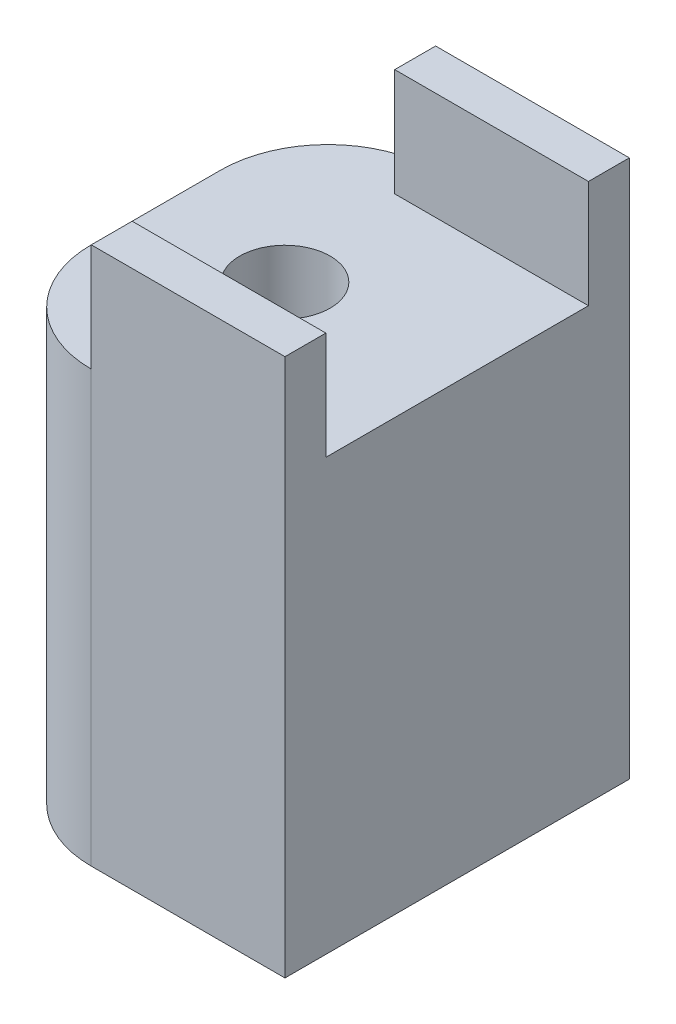
SolidWorks part; units mm, degrees
ref_plane "Front Plane" through (0, 0, 0) normal (0, 0, 1) x (1, 0, 0)
ref_plane "Top Plane" through (0, 0, 0) normal (0, 1, 0) x (1, 0, 0)
ref_plane "Right Plane" through (0, 0, 0) normal (1, 0, 0) x (0, 0, -1)
sketch "Sketch1" plane through (0, 0, 0) normal (0, 1, 0) x (1, 0, 0)
  line L5 (-6, 8) -> (6, 8)
  line L6 (-6, 8) -> (-6, -8)
  line L7 (-6, -8) -> (6, -8)
  line L8 (6, 8) -> (6, -8)
  line L9 (-6, 8) -> (6, -8) construction
  line L10 (-6, -8) -> (6, 8) construction
  line L11 (6, 8) -> (8, 8)
  line L12 (6, 8) -> (6, -8)
  line L13 (6, -8) -> (8, -8)
  line L14 (8, 8) -> (8, -8)
  circle A0 centre (0, 0) radius 2.1
  point P0 (0, 0)
  dimension "D1" = 4.2
  dimension "D2" = 16
  dimension "D3" = 6
  dimension "D4" = 2
extrude "Boss-Extrude1" add sketch "Sketch1" along normal blind 20 contours L8 L5 L6 L7 A0 | L14 L11 L8 L13
fillet "Fillet1" radius 5 2 edges at (-6, 10, -8) (-6, 10, 8)
sketch "Sketch2" plane through (0, 20, 0) normal (0, 1, 0) x (1, 0, 0)
  line L0 (8, 0) -> (-6, 0) construction
  line L1 (8, 8) -> (-1, 8)
  line L2 (8, 8) -> (8, 6.1)
  line L3 (8, 6.1) -> (-1, 6.1)
  line L4 (-1, 8) -> (-1, 6.1)
  line L5 (8, 8) -> (8, -8) construction
  line L6 (-6, 3) -> (-6, -3) construction
  line L7 (-1, -8) -> (-1, -6.1)
  line L8 (8, -6.1) -> (-1, -6.1)
  line L9 (8, -8) -> (8, -6.1)
  line L10 (8, -8) -> (-1, -8)
  dimension "D1" = 1.9
extrude "Boss-Extrude2" add sketch "Sketch2" along normal blind 5
